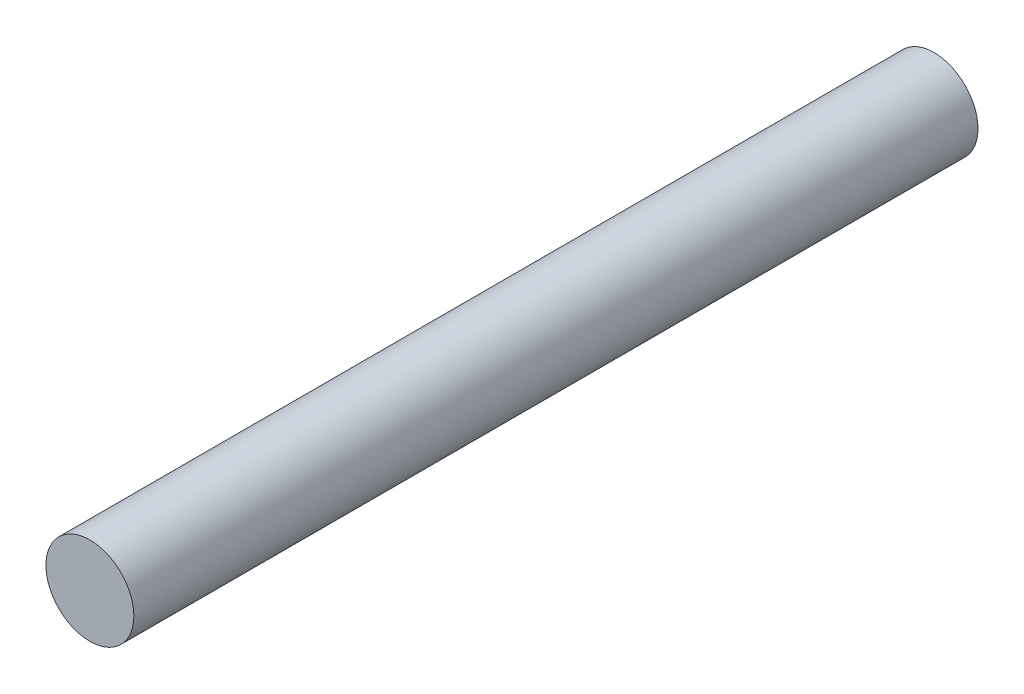
SolidWorks part; units mm, degrees
material "Temperguss"
ref_plane "Ebene vorne" through (0, 0, 0) normal (0, 0, 1) x (1, 0, 0)
ref_plane "Ebene oben" through (0, 0, 0) normal (0, 1, 0) x (1, 0, 0)
ref_plane "Ebene rechts" through (0, 0, 0) normal (1, 0, 0) x (0, 0, -1)
sketch "Skizze1" plane through (0, 0, 0) normal (0, 0, 1) x (1, 0, 0)
  circle A0 centre (-4.1799, 1.2472) radius 1.25
  dimension "D1" = 2.5
extrude "Aufsatz-Linear austragen1" add sketch "Skizze1" along normal blind 24
